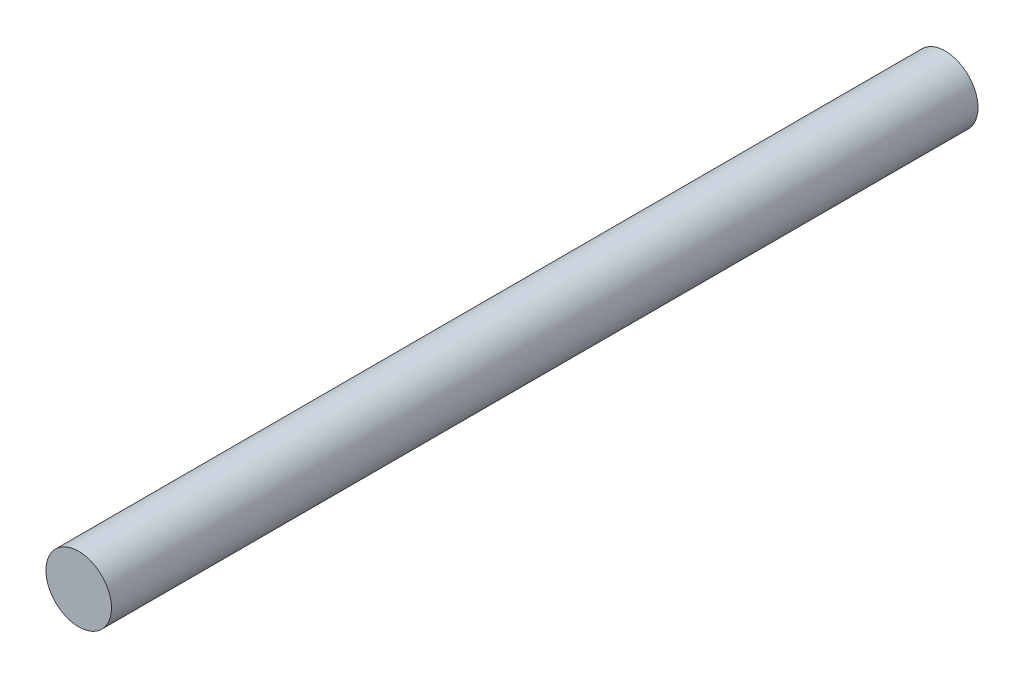
SolidWorks part; units mm, degrees
ref_plane "Front Plane" through (0, 0, 0) normal (0, 0, 1) x (1, 0, 0)
ref_plane "Top Plane" through (0, 0, 0) normal (0, 1, 0) x (1, 0, 0)
ref_plane "Right Plane" through (0, 0, 0) normal (1, 0, 0) x (0, 0, -1)
sketch "Sketch3" plane through (0, 0, 0) normal (0, 0, 1) x (1, 0, 0)
  circle A0 centre (0, 0) radius 7.45
  dimension "D1" = 14.9
extrude "Boss-Extrude1" add sketch "Sketch3" along normal blind 197
